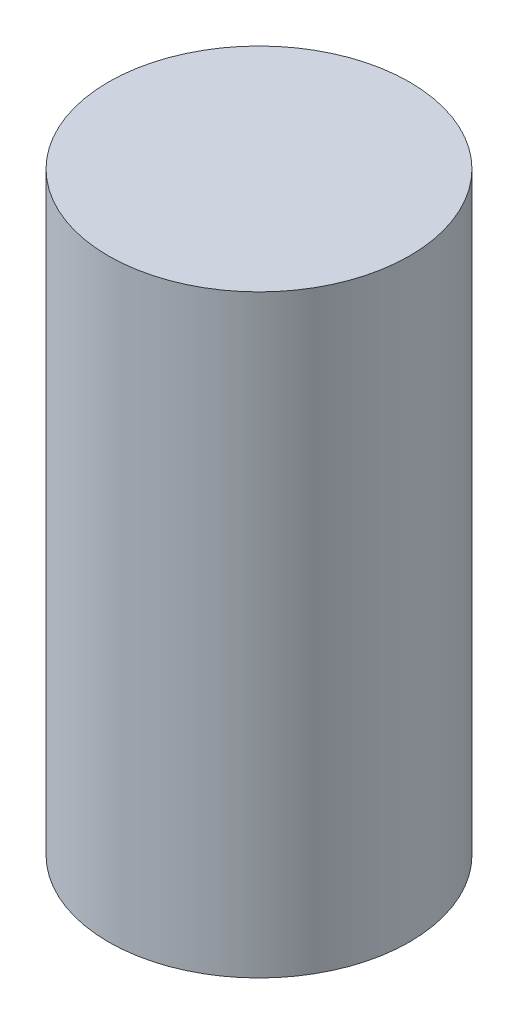
SolidWorks part; units mm, degrees
ref_plane "Front Plane" through (0, 0, 0) normal (0, 0, 1) x (1, 0, 0)
ref_plane "Top Plane" through (0, 0, 0) normal (0, 1, 0) x (1, 0, 0)
ref_plane "Right Plane" through (0, 0, 0) normal (1, 0, 0) x (0, 0, -1)
sketch "Sketch1" plane through (0, 0, 0) normal (0, 1, 0) x (1, 0, 0)
  line L0 (0, 0) -> (5.5, 0) construction
  circle A0 centre (0, 0) radius 5.5
  dimension "D1" = 11
extrude "Boss-Extrude1" add sketch "Sketch1" along normal blind 21.7 contours A0
